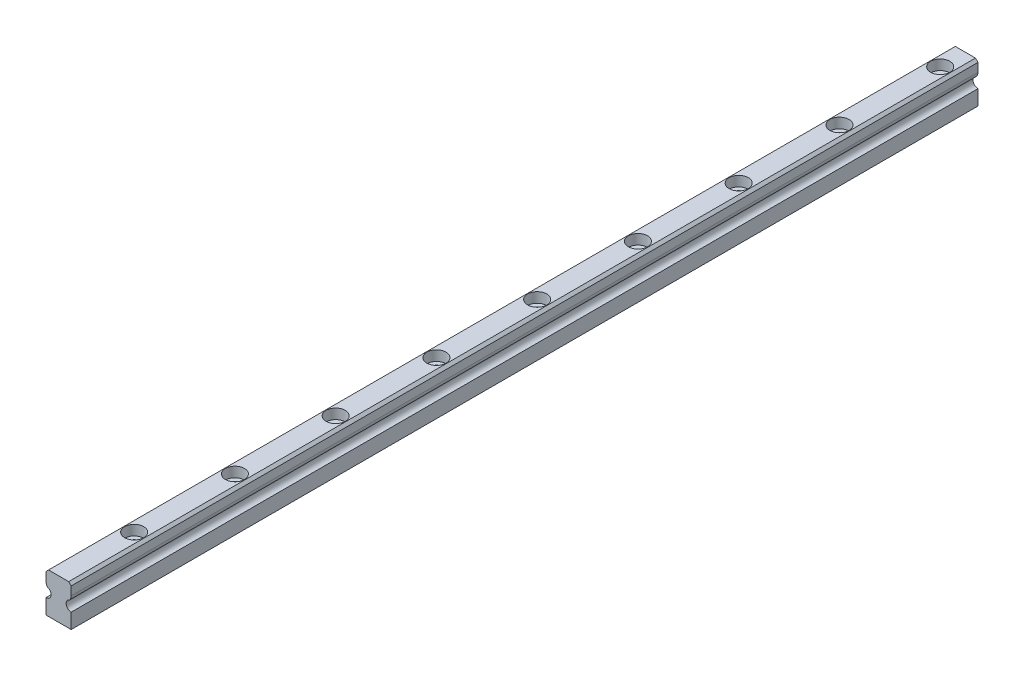
SolidWorks part; units mm, degrees
ref_plane "Front Plane" through (0, 0, 0) normal (0, 0, 1) x (1, 0, 0)
ref_plane "Top Plane" through (0, 0, 0) normal (0, 1, 0) x (1, 0, 0)
ref_plane "Right Plane" through (0, 0, 0) normal (1, 0, 0) x (0, 0, -1)
sketch "Sketch1" plane through (0, 0, 0) normal (0, 0, 1) x (1, 0, 0)
  line L1 (2.5, 4) -> (-2.5, 4)
  line L2 (2.5, 4) -> (2.5, -4)
  line L3 (2.5, -4) -> (-2.5, -4)
  line L4 (-2.5, 4) -> (-2.5, -4)
  line L5 (2.5, 4) -> (-2.5, -4) construction
  line L6 (2.5, -4) -> (-2.5, 4) construction
  point P0 (0, 0)
  dimension "D1" = 5
  dimension "D2" = 8
extrude "Boss-Extrude1" add sketch "Sketch1" along normal blind 185
sketch "Sketch2" plane through (0, 0, 0) normal (0, 0, -1) x (-1, 0, 0)
  line L0 (-2.5, 4) -> (-2.5, 1.7982)
  line L4 (-2.5, 4) -> (2.5, 4)
  line L6 (-2.5, -4) -> (-2.5, 4) construction
  line L8 (2.5, 4) -> (2.5, 1.7982)
  line L9 (2.5, -4) -> (-2.5, -4)
  line L10 (-2.5, -4) -> (-2.5, -1)
  line L12 (2.5, -1) -> (2.5, -4)
  arc A4 (-2.5, -1) -> (-2.2014, 0.9544) centre (-2.5, 0) ccw
  arc A5 (-2.5, 1.7982) -> (-2.2014, 0.9544) centre (-1.1583, 1.7982) ccw
  arc A6 (2.5, 1.7982) -> (2.2014, 0.9544) centre (1.1583, 1.7982) cw
  arc A7 (2.5, -1) -> (2.2014, 0.9544) centre (2.5, 0) cw
extrude "Boss-Extrude2" add sketch "Sketch2" along normal blind 200
sketch "Sketch3" plane through (0, 0, 185) normal (0, 0, 1) x (1, 0, 0)
  line L4 (-2.5, 4) -> (-2.5, -4)
  line L5 (-2.5, -4) -> (2.5, -4)
  line L6 (2.5, -4) -> (2.5, 4)
  line L7 (2.5, 4) -> (-2.5, 4)
  line L8 (-2.5, 4) -> (-2.5, -4)
  line L9 (-2.5, -4) -> (2.5, -4)
  line L10 (2.5, -4) -> (2.5, 4)
  line L11 (2.5, 4) -> (-2.5, 4)
  dimension "D1" = 0
extrude "Cut-Extrude1" cut sketch "Sketch3" against normal blind 200
sketch "Sketch4" plane through (0, -4, 0) normal (0, -1, 0) x (1, 0, 0)
  line L0 (-2.5, -15) -> (2.5, -15) construction
  circle A0 centre (0, -35) radius 1
  circle A1 centre (0, -55) radius 1
  circle A2 centre (0, -75) radius 1
  circle A3 centre (0, -95) radius 1
  circle A4 centre (0, -115) radius 1
  circle A5 centre (0, -135) radius 1
  circle A6 centre (0, -155) radius 1
  circle A7 centre (0, -175) radius 1
  circle A8 centre (0, -195) radius 1
  dimension "D1" = 20
  dimension "D2" = 9
extrude "Cut-Extrude2" cut sketch "Sketch4" against normal up to next
sketch "Sketch5" plane through (0, 4, 0) normal (0, 1, 0) x (1, 0, 0)
  circle A0 centre (0, 195) radius 1.9
  circle A1 centre (0, 175) radius 1.9
  circle A2 centre (0, 155) radius 1.9
  circle A3 centre (0, 135) radius 1.9
  circle A4 centre (0, 115) radius 1.9
  circle A5 centre (0, 95) radius 1.9
  circle A6 centre (0, 75) radius 1.9
  circle A7 centre (0, 55) radius 1.9
  circle A8 centre (0, 35) radius 1.9
  dimension "D1" = 9
extrude "Cut-Extrude3" cut sketch "Sketch5" against normal blind 2
chamfer "Chamfer1" distance 0.5 angle 45 1 edges at (-2.5, 4, -107.5)
chamfer "Chamfer2" distance 0.5 angle 45 1 edges at (2.5, 4, -107.5)
sketch "Sketch6" plane through (0, 0, -15) normal (0, 0, 1) x (1, 0, 0)
  line L8 (2.5, 1.7982) -> (2.5, 3.5)
  line L9 (2.5, 3.5) -> (2, 4)
  line L10 (2, 4) -> (-2, 4)
  line L11 (-2, 4) -> (-2.5, 3.5)
  line L12 (-2.5, 3.5) -> (-2.5, 1.7982)
  line L13 (-2.5, -1) -> (-2.5, -4)
  line L14 (-2.5, -4) -> (2.5, -4)
  line L15 (2.5, -4) -> (2.5, -1)
  line L16 (2.5, 1.7982) -> (2.5, 3.5)
  line L17 (2.5, 3.5) -> (2, 4)
  line L18 (2, 4) -> (-2, 4)
  line L19 (-2, 4) -> (-2.5, 3.5)
  line L20 (-2.5, 3.5) -> (-2.5, 1.7982)
  line L21 (-2.5, -1) -> (-2.5, -4)
  line L22 (-2.5, -4) -> (2.5, -4)
  line L23 (2.5, -4) -> (2.5, -1)
  arc A4 (-2.5, 1.7982) -> (-2.2014, 0.9544) centre (-1.1583, 1.7982) ccw
  arc A5 (-2.5, -1) -> (-2.2014, 0.9544) centre (-2.5, 0) ccw
  arc A6 (2.2014, 0.9544) -> (2.5, -1) centre (2.5, 0) ccw
  arc A7 (2.2014, 0.9544) -> (2.5, 1.7982) centre (1.1583, 1.7982) ccw
  arc A8 (-2.5, 1.7982) -> (-2.2014, 0.9544) centre (-1.1583, 1.7982) ccw
  arc A9 (-2.5, -1) -> (-2.2014, 0.9544) centre (-2.5, 0) ccw
  arc A10 (2.2014, 0.9544) -> (2.5, -1) centre (2.5, 0) ccw
  arc A11 (2.2014, 0.9544) -> (2.5, 1.7982) centre (1.1583, 1.7982) ccw
  dimension "D1" = 0
extrude "Cut-Extrude4" cut sketch "Sketch6" against normal blind 5
